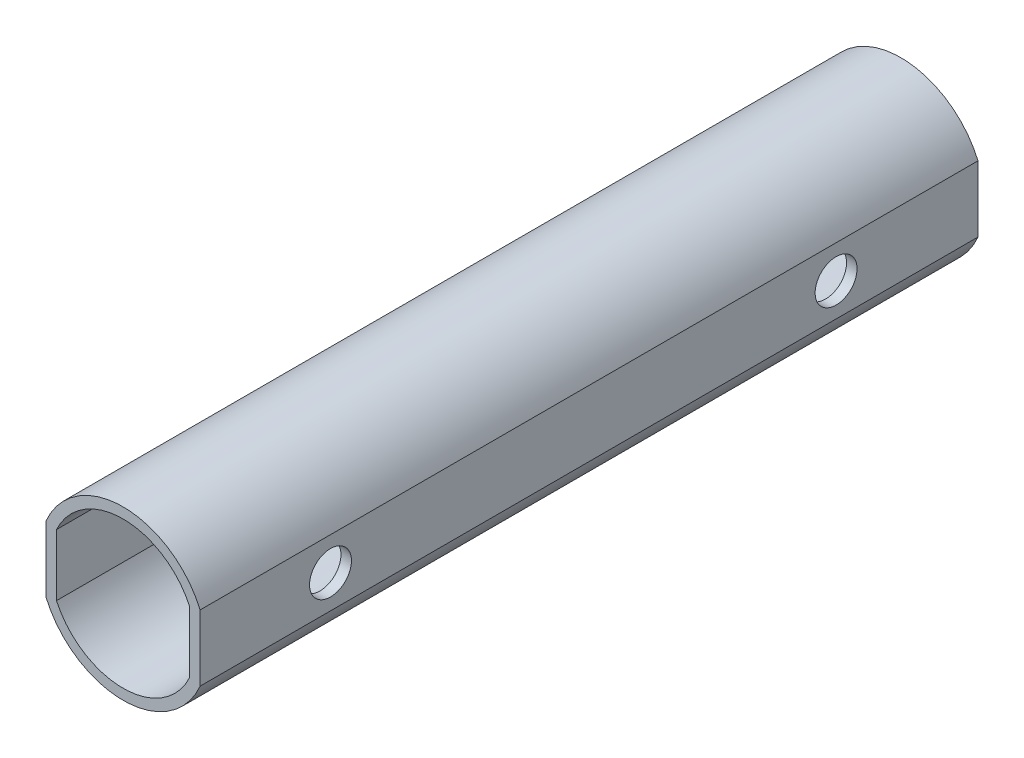
SolidWorks part; units mm, degrees
material "6061-T6 (SS)"
ref_plane "Front Plane" through (0, 0, 0) normal (0, 0, 1) x (1, 0, 0)
ref_plane "Top Plane" through (0, 0, 0) normal (0, 1, 0) x (1, 0, 0)
ref_plane "Right Plane" through (0, 0, 0) normal (1, 0, 0) x (0, 0, -1)
sketch "Sketch1" plane through (0, 0, 0) normal (0, 0, 1) x (1, 0, 0)
  line L0 (10.0868, 4.663) -> (10.0868, -4.663)
  line L1 (11.6743, 5) -> (11.6743, -5)
  line L2 (-10.0868, 4.663) -> (-10.0868, -4.663)
  line L4 (10.0868, 4.663) -> (-10.0868, 4.663) construction
  line L5 (10.0868, -4.663) -> (-10.0868, -4.663) construction
  line L6 (11.6743, -5) -> (-11.6743, -5) construction
  line L7 (11.6743, 5) -> (-11.6743, 5) construction
  line L8 (-11.6743, 5) -> (-11.6743, -5)
  arc A0 (11.6743, 5) -> (-11.6743, 5) centre (0, 0) ccw
  arc A1 (10.0868, 4.663) -> (-10.0868, 4.663) centre (0, 0) ccw
  arc A2 (-10.0868, -4.663) -> (10.0868, -4.663) centre (0, 0) ccw
  arc A3 (-11.6743, -5) -> (11.6743, -5) centre (0, 0) ccw
  dimension "D1" = 25.4
  dimension "D2" = 1.5875
  dimension "D3" = 10
  dimension "D4" = 9.326
extrude "Boss-Extrude1" add sketch "Sketch1" along normal blind 117.85
sketch "Sketch2" plane through (11.6743, 0, 0) normal (1, 0, 0) x (0, 0, -1)
  line L0 (-117.85, 5) -> (0, 5) construction
  line L1 (-117.85, -5) -> (-117.85, 5) construction
  line L2 (0, -5) -> (0, 5) construction
  circle A0 centre (-21.5, 0) radius 3.175
  circle A1 centre (-98.1, 0) radius 3.175
  dimension "D2" = 6.35
  dimension "D3" = 6.35
  dimension "D1" = 5
  dimension "D4" = 5
  dimension "D5" = 19.75
  dimension "D6" = 21.5
extrude "Cut-Extrude1" cut sketch "Sketch2" against normal up to surface (23.3487 mm away) up to face at (-11.6743, 0, 58.925)
